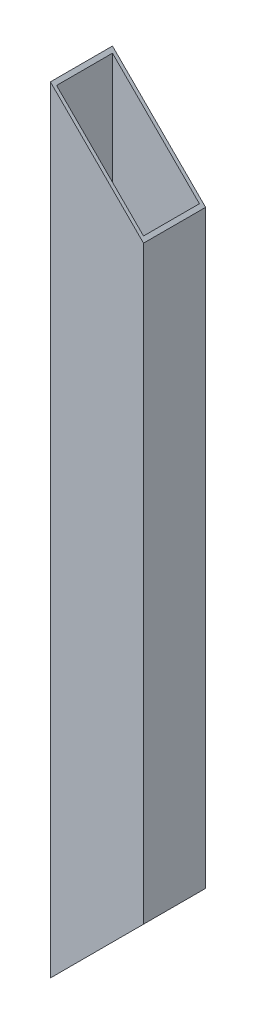
SolidWorks part; units mm, degrees
ref_plane "Ön Düzlem" through (0, 0, 0) normal (0, 0, 1) x (1, 0, 0)
ref_plane "Üst Düzlem" through (0, 0, 0) normal (0, 1, 0) x (1, 0, 0)
ref_plane "Sağ Düzlem" through (0, 0, 0) normal (1, 0, 0) x (0, 0, -1)
sketch "Çizim1" plane through (0, 0, 0) normal (0, 1, 0) x (1, 0, 0)
  line L1 (0, 0) -> (60, 0)
  line L2 (0, 0) -> (0, 40)
  line L3 (0, 40) -> (60, 40)
  line L4 (60, 0) -> (60, 40)
  line L9 (2, 38) -> (58, 38)
  line L10 (2, 38) -> (2, 2)
  line L11 (2, 2) -> (58, 2)
  line L12 (58, 38) -> (58, 2)
  dimension "D1" = 60
  dimension "D2" = 40
  dimension "D3" = 2
  dimension "D4" = 2
  dimension "D5" = 2
  dimension "D6" = 2
extrude "Yükseklik-Ekstrüzyon1" add sketch "Çizim1" along normal blind 500
sketch "Çizim2" plane through (0, 0, -40) normal (0, 0, -1) x (-1, 0, 0)
  line L0 (0, 500) -> (-60, 440)
  line L1 (-60, 500) -> (-60, 0) construction
  line L2 (0, 0) -> (-60, 60)
  line L6 (-60, 0) -> (0, 0)
  line L7 (0, 0) -> (0, 500)
  line L8 (0, 500) -> (-60, 500)
  line L9 (-60, 500) -> (-60, 0)
  line L10 (-60, 0) -> (0, 0)
  line L11 (0, 0) -> (0, 500)
  line L12 (0, 500) -> (-60, 500)
  line L13 (-60, 500) -> (-60, 0)
  line M7 (-60, 0) -> (0, 0)
  line M9 (0, 500) -> (-60, 500)
  line M10 (-60, 500) -> (-60, 0)
  dimension "D2" = 45
  dimension "D3" = 45
  dimension "D1" = 0
extrude "Kes-Ekstrüzyon1" cut sketch "Çizim2" against normal blind 700 contours L0 M9 M10 | L2 M7 M10
